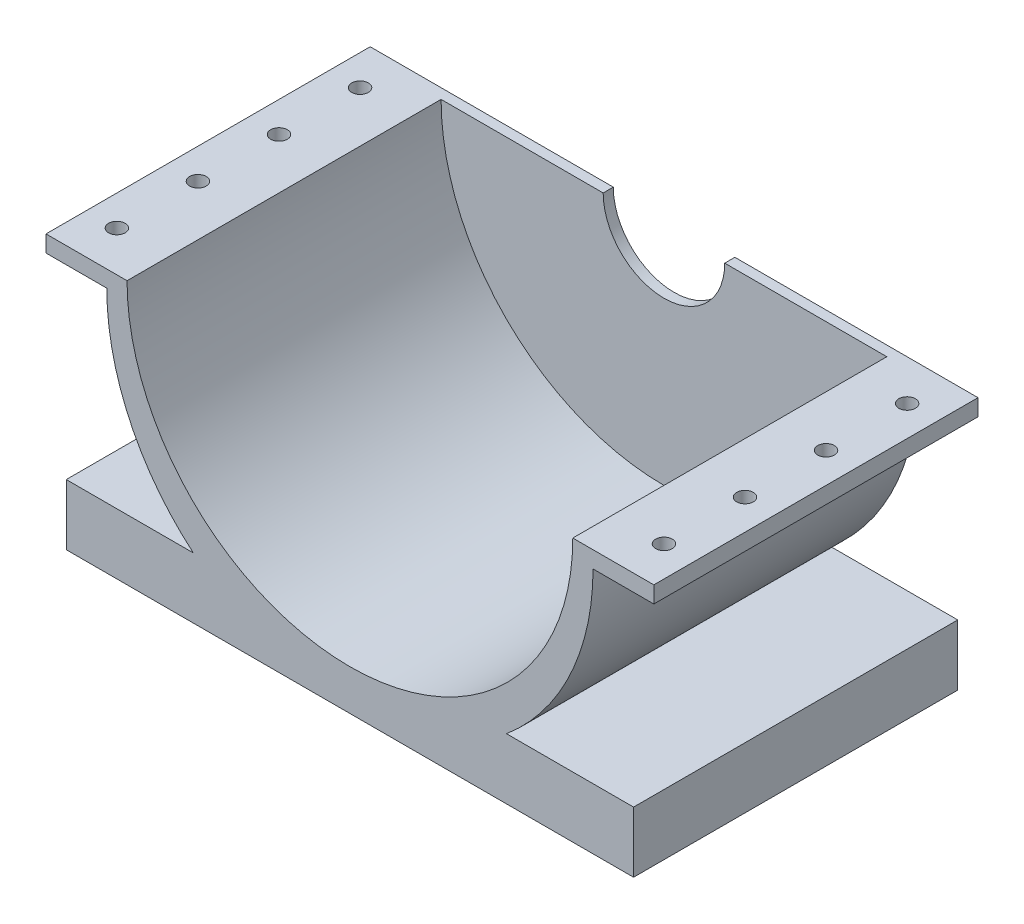
SolidWorks part; units mm, degrees
material "Gray Cast Iron"
ref_plane "Front Plane" through (0, 0, 0) normal (0, 0, 1) x (1, 0, 0)
ref_plane "Top Plane" through (0, 0, 0) normal (0, 1, 0) x (1, 0, 0)
ref_plane "Right Plane" through (0, 0, 0) normal (1, 0, 0) x (0, 0, -1)
sketch "Sketch1" plane through (0, 0, 0) normal (0, 0, 1) x (1, 0, 0)
  line L0 (7.5, 0) -> (6, 0)
  line L1 (7.5, 0.41) -> (-7.5, 0.41)
  line L2 (-7.5, 0.41) -> (-7.5, 0)
  line L3 (7.5, 0.41) -> (7.5, 0)
  line L4 (-6, 0) -> (-7.5, 0)
  line L5 (7.5, 0) -> (-7.5, 0) construction
  line L6 (-7, -6.09) -> (7, -6.09)
  line L7 (-7, -4.59) -> (-3.8642, -4.59)
  line L8 (-7, -4.59) -> (-7, -6.09)
  line L9 (7, -4.59) -> (7, -6.09)
  line L10 (3.8642, -4.59) -> (7, -4.59)
  line L11 (-7, -4.59) -> (7, -4.59) construction
  arc A0 (-6, 0) -> (-3.8642, -4.59) centre (0, 0) ccw
  arc A1 (3.8642, -4.59) -> (6, 0) centre (0, 0) ccw
  point P6 (0, 0)
  point P12 (0, -6.09)
  dimension "D1" = 12
  dimension "D2" = 15
  dimension "D3" = 0.41
  dimension "D4" = 1.5
  dimension "D5" = 1.5
  dimension "D6" = 6.5
  dimension "D7" = 14
  dimension "D8" = 1.5
extrude "Boss-Extrude1" add sketch "Sketch1" along normal mid plane 8
sketch "Sketch2" plane through (0, 0, 4) normal (0, 0, 1) x (1, 0, 0)
  line L0 (7.5, 0.41) -> (-7.5, 0.41) construction
  line L1 (-5.5, 0.41) -> (5.5, 0.41)
  arc A0 (-5.5, 0.41) -> (5.5, 0.41) centre (0, 0.41) ccw
  dimension "D1" = 11
extrude "Cut-Extrude1" cut sketch "Sketch2" against normal blind 7.75
sketch "Sketch3" plane through (0, 0, -4) normal (0, 0, -1) x (-1, 0, 0)
  line L0 (-7.5, 0.41) -> (7.5, 0.41) construction
  line L1 (-1.5, 0.41) -> (1.5, 0.41)
  arc A0 (-1.5, 0.41) -> (1.5, 0.41) centre (0, 0.41) ccw
  dimension "D1" = 3
extrude "Cut-Extrude2" cut sketch "Sketch3" against normal blind 7.75
sketch "Sketch4" plane through (0, 0.41, 0) normal (0, 1, 0) x (1, 0, 0)
  line L0 (7.5, -4) -> (5.5, -4) construction
  line L2 (7.5, -4) -> (7.5, 4) construction
  circle A0 centre (6.75, 3) radius 0.205
  circle A1 centre (6.75, 1) radius 0.205
  circle A2 centre (6.75, -1) radius 0.205
  circle A3 centre (6.75, -3) radius 0.205
  dimension "D1" = 0.41
  dimension "D2" = 0.41
  dimension "D3" = 0.41
  dimension "D4" = 0.41
  dimension "D5" = 1
  dimension "D6" = 0.75
  dimension "D7" = 2
  dimension "D8" = 2
  dimension "D9" = 2
extrude "Cut-Extrude3" cut sketch "Sketch4" against normal blind 2.75
mirror "Mirror1" about plane through (0, 0, 0) normal (1, 0, 0) of "Cut-Extrude3"
